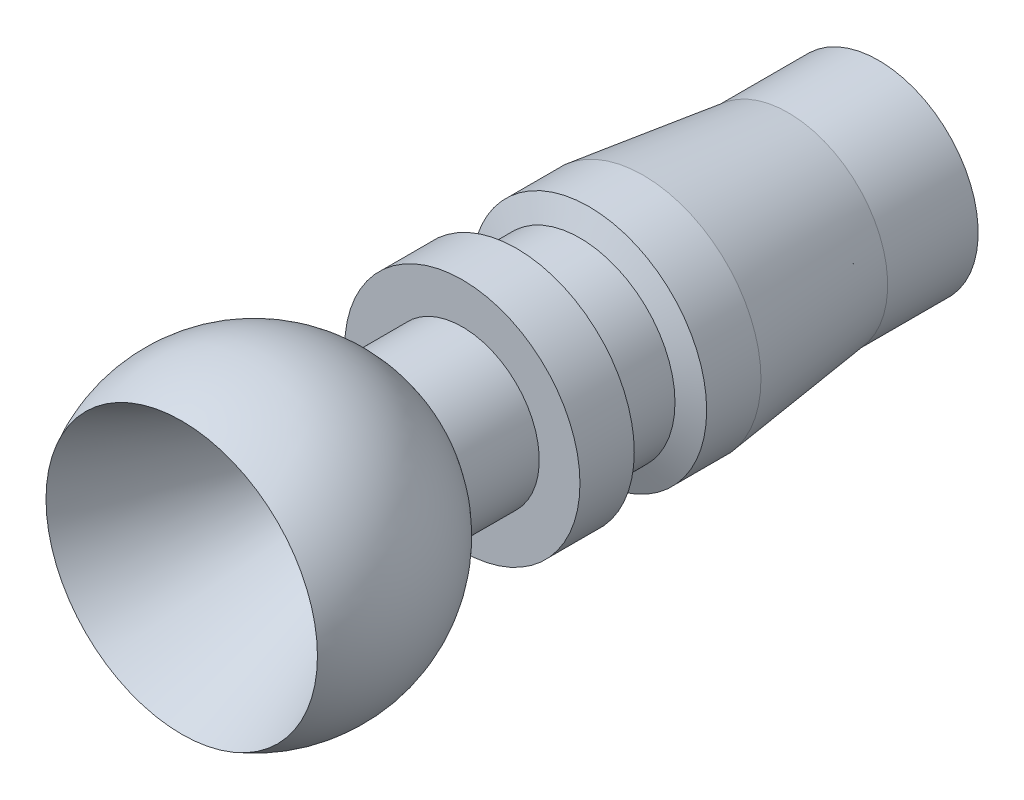
SolidWorks part; units mm, degrees
material "Plain Carbon Steel"
ref_plane "Front Plane" through (0, 0, 0) normal (0, 0, 1) x (1, 0, 0)
ref_plane "Top Plane" through (0, 0, 0) normal (0, 1, 0) x (1, 0, 0)
ref_plane "Right Plane" through (0, 0, 0) normal (1, 0, 0) x (0, 0, -1)
ref_axis "Axis1" through (0, 0, -88.99) along (0, 0, 1)
sketch "Sketch3" plane through (0, 0, 0) normal (0, 1, 0) x (1, 0, 0)
  line L0 (2.5, 0) -> (5.5, 0)
  line L1 (5.5, 0) -> (5.5, -5)
  line L2 (5.5, -5) -> (5.5, -13) construction
  line L3 (5.5, -13) -> (6.5, -13) construction
  line L4 (5.5, -5) -> (6.5, -13)
  line L5 (6.5, -13) -> (6.5, -16)
  line L6 (6.5, -16) -> (5.25, -16) construction
  line L7 (5.25, -16) -> (5.25, -16.5) construction
  line L8 (6.5, -16) -> (5.25, -16.5)
  line L9 (5.25, -16.5) -> (5.25, -20)
  line L10 (5.25, -20) -> (6.5, -20)
  line L11 (6.5, -20) -> (6.5, -23)
  line L12 (6.5, -23) -> (4.25, -23)
  line L13 (4.25, -23) -> (4.25, -26)
  line L14 (0, 0) -> (2.5, 0) construction
  line L15 (0, 88.99) -> (0, -88.99) construction
  line L18 (4.25, -26) -> (4.25, -27.1388)
  line L20 (2.5, 0) -> (2.5, -27.1388)
  line L21 (2.5, -27.1388) -> (7.4986, -38.5026)
  arc A0 (7.4986, -38.5026) -> (4.25, -27.1388) centre (0, -34.5) ccw
  dimension "D14" = 8.5
  dimension "D2" = 5
  dimension "D3" = 8
  dimension "D4" = 1
  dimension "D5" = 3
  dimension "D6" = 1.25
  dimension "D7" = 0.5
  dimension "D8" = 3.5
  dimension "D9" = 3
  dimension "D10" = 2.25
  dimension "D11" = 3
  dimension "D12" = 2.5
  dimension "D13" = 3
revolve "Revolve1" add sketch "Sketch3" angle 360 about axis through (0, 0, -88.99) along (0, 0, 1)
